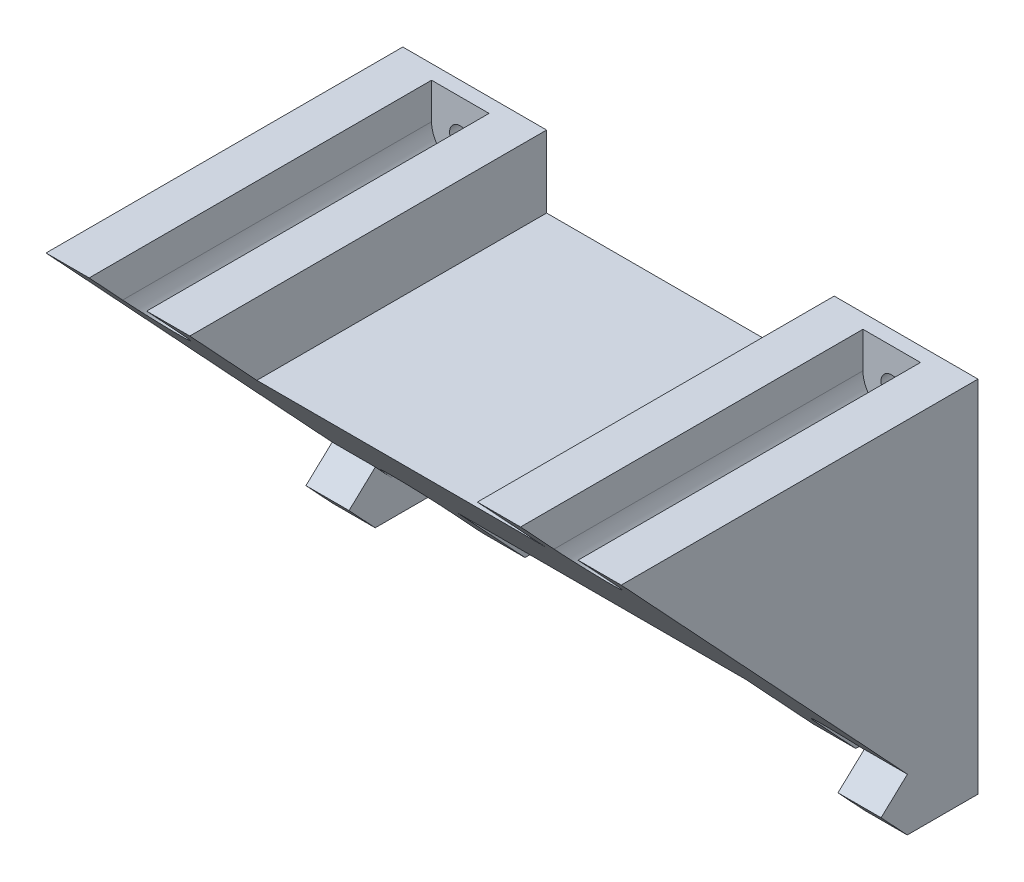
SolidWorks part; units mm, degrees
ref_plane "前视基准面" through (0, 0, 0) normal (0, 0, 1) x (1, 0, 0)
ref_plane "上视基准面" through (0, 0, 0) normal (0, 1, 0) x (1, 0, 0)
ref_plane "右视基准面" through (0, 0, 0) normal (1, 0, 0) x (0, 0, -1)
sketch "草图1" plane through (0, 0, 0) normal (0, 0, 1) x (1, 0, 0)
  line L0 (0, 0) -> (0, 50)
  line L1 (20, 50) -> (20, 40)
  line L2 (60, 40) -> (20, 40)
  line L3 (60, 50) -> (60, 40)
  line L4 (20, 50) -> (0, 50)
  line L5 (60, 50) -> (80, 50)
  line L6 (80, 50) -> (80, 0)
  line L7 (80, 0) -> (60, 0)
  line L8 (60, 0) -> (60, 10)
  line L9 (60, 10) -> (20, 10)
  line L10 (20, 10) -> (20, 0)
  line L11 (20, 0) -> (0, 0)
  point P13 (0, 0)
  point P14 (0, 0)
  dimension "D1" = 50
  dimension "D2" = 20
  dimension "D3" = 40
  dimension "D4" = 20
  dimension "D5" = 20
  dimension "D6" = 40
  dimension "D7" = 20
  dimension "D8" = 10
  dimension "D10" = 10
extrude "凸台-拉伸2" add sketch "草图1" along normal blind 2
sketch "草图3" plane through (0, 0, 2) normal (0, 0, 1) x (1, 0, 0)
  line L0 (10, 5) -> (10, 0) construction
  line L2 (20, 0) -> (0, 0) construction
  line L3 (10, 50) -> (10, 45) construction
  line L4 (20, 50) -> (0, 50) construction
  line L5 (70, 50) -> (70, 45) construction
  line L6 (60, 50) -> (80, 50) construction
  line L7 (70, 0) -> (70, 5) construction
  line L8 (80, 0) -> (60, 0) construction
  circle A1 centre (10, 45) radius 1.5
  circle A2 centre (10, 5) radius 1.5
  circle A3 centre (70, 45) radius 1.5
  circle A4 centre (70, 5) radius 1.5
  point P20 (0, 0)
  dimension "D1" = 3
  dimension "D4" = 3
  dimension "D5" = 3
  dimension "D6" = 3
  dimension "D2" = 40
  dimension "D3" = 40
  dimension "D7" = 60
  dimension "D8" = 60
  dimension "D9" = 10
  dimension "D10" = 10
  dimension "D11" = 10
  dimension "D12" = 10
extrude "切除-拉伸1" cut sketch "草图3" against normal through all
sketch "草图5" plane through (0, 0, 2) normal (0, 0, 1) x (1, 0, 0)
  line L0 (0, 50) -> (6, 50)
  line L1 (20, 50) -> (0, 50) construction
  line L2 (6, 50) -> (6, 45)
  line L3 (14, 45) -> (14, 50)
  line L4 (14, 50) -> (20, 50)
  line L5 (20, 50) -> (20, 40)
  line L6 (20, 40) -> (60, 40)
  line L7 (60, 40) -> (60, 50)
  line L8 (60, 50) -> (66, 50)
  line L9 (60, 50) -> (80, 50) construction
  line L10 (66, 50) -> (66, 45)
  line L11 (74, 45) -> (74, 50)
  line L12 (74, 50) -> (80, 50)
  line L13 (80, 50) -> (80, 0)
  line L14 (80, 0) -> (74, 0)
  line L15 (80, 0) -> (60, 0) construction
  line L16 (74, 0) -> (74, 5)
  line L17 (66, 5) -> (66, 0)
  line L18 (66, 0) -> (60, 0)
  line L19 (60, 0) -> (60, 10)
  line L20 (60, 10) -> (20, 10)
  line L21 (20, 10) -> (20, 0)
  line L22 (20, 0) -> (14, 0)
  line L23 (20, 0) -> (0, 0) construction
  line L24 (14, 0) -> (14, 5)
  line L25 (6, 5) -> (6, 0)
  line L26 (6, 0) -> (0, 0)
  line L27 (0, 0) -> (0, 50)
  arc A0 (6, 45) -> (14, 45) centre (10, 45) ccw
  arc A1 (66, 45) -> (74, 45) centre (70, 45) ccw
  arc A2 (74, 5) -> (66, 5) centre (70, 5) ccw
  arc A3 (14, 5) -> (6, 5) centre (10, 5) ccw
  dimension "D5" = 4
  dimension "D6" = 4
  dimension "D7" = 4
  dimension "D8" = 4
  dimension "D1" = 5
  dimension "D2" = 5
  dimension "D3" = 5
  dimension "D4" = 5
  dimension "D9" = 10
  dimension "D10" = 10
  dimension "D11" = 10
  dimension "D12" = 10
extrude "凸台-拉伸3" add sketch "草图5" along normal blind 1
draft "拔模4" type of draft neutral plane draft angle 43 faces to draft 1 face at (40, 25, 3) neutral plane through (20, 0, 2) neutral plane normal (0, -1, 0) parameters "D1"=43
sketch "草图6" plane through (0, -1.4963, 1.6046) normal (0, -0.682, 0.7314) x (1, 0, 0)
  line L0 (6, 2.046) -> (6, 12.046)
  line L1 (6, 2.046) -> (6, 8.8826) construction
  line L2 (6, 12.046) -> (0, 12.046)
  line L3 (0, 70.4124) -> (0, 2.046) construction
  line L4 (0, 12.046) -> (0, 2.046)
  line L5 (0, 2.046) -> (6, 2.046)
  dimension "D1" = 10
  dimension "D2" = 6
extrude "凸台-拉伸4" add sketch "草图6" along normal blind 5
sketch "草图7" plane through (0, -1.4963, 1.6046) normal (0, -0.682, 0.7314) x (1, 0, 0)
  line L0 (74, 2.046) -> (80, 2.046)
  line L1 (80, 2.046) -> (80, 12.046)
  line L2 (80, 2.046) -> (80, 70.4124) construction
  line L3 (80, 12.046) -> (74, 12.046)
  line L4 (74, 12.046) -> (74, 2.046)
  dimension "D1" = 10
  dimension "D2" = 6
extrude "凸台-拉伸5" add sketch "草图7" along normal blind 5 contours L4 L0 L1 L3
sketch "草图8" plane through (80, 0, 0) normal (1, 0, 0) x (0, 0, -1)
  line L0 (-3, 0) -> (-9.8366, 0)
  line L1 (-6.6568, -3.41) -> (-13.4768, 3.9035) construction
  line L2 (-9.8366, 0) -> (-6.6568, -3.41)
  line L3 (-6.6568, -3.41) -> (-3, 0)
extrude "切除-拉伸2" cut sketch "草图8" against normal through all
